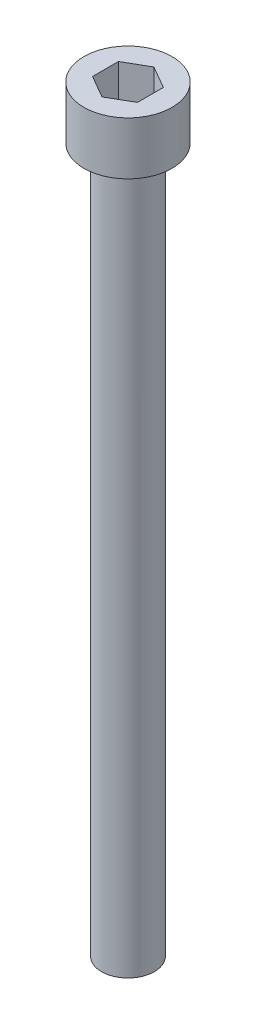
SolidWorks part; units mm, degrees
ref_plane "Спереди" through (0, 0, 0) normal (0, 0, 1) x (1, 0, 0)
ref_plane "Сверху" through (0, 0, 0) normal (0, 1, 0) x (1, 0, 0)
ref_plane "Справа" through (0, 0, 0) normal (1, 0, 0) x (0, 0, -1)
sketch "Эскиз1" plane through (0, 0, 0) normal (0, 1, 0) x (1, 0, 0)
  line L1 (0, -2.9445) -> (2.55, -1.4722)
  line L2 (2.55, -1.4722) -> (2.55, 1.4722)
  line L3 (2.55, 1.4722) -> (0, 2.9445)
  line L4 (0, 2.9445) -> (-2.55, 1.4722)
  line L5 (-2.55, 1.4722) -> (-2.55, -1.4722)
  line L6 (-2.55, -1.4722) -> (0, -2.9445)
  circle A0 centre (0, 0) radius 5
  circle A1 centre (0, 0) radius 2.55 construction
  dimension "D1" = 5.1
extrude "Вытянуть1" add sketch "Эскиз1" along normal blind 6
sketch "Эскиз2" plane through (0, 0, 0) normal (0, -1, 0) x (1, 0, 0)
  circle A0 centre (0, 0) radius 3
extrude "Вытянуть2" add sketch "Эскиз2" along normal blind 80
